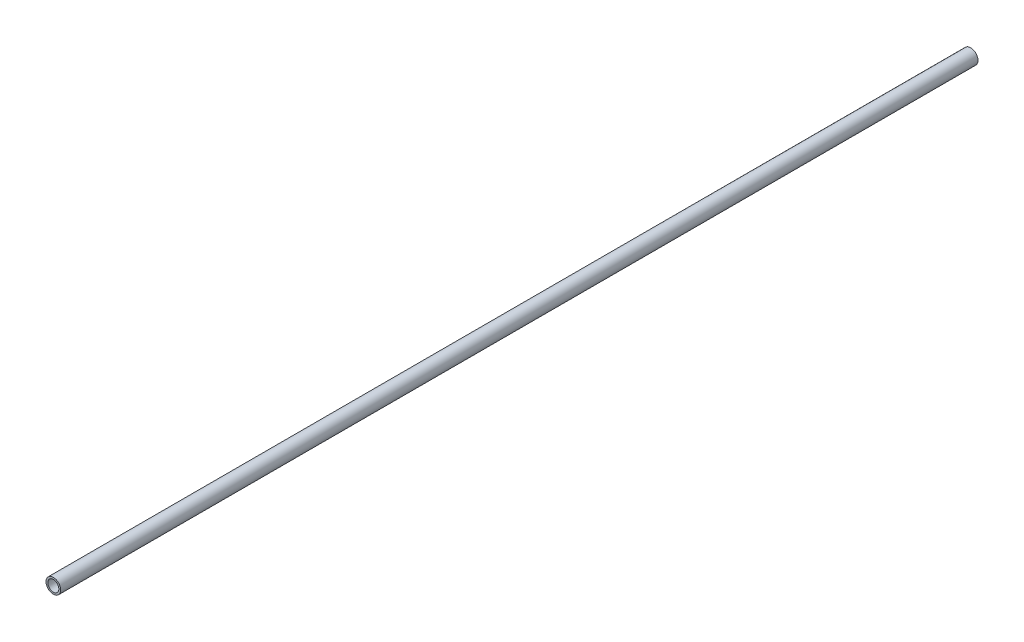
SolidWorks part; units mm, degrees
ref_plane "Płaszczyzna przednia" through (0, 0, 0) normal (0, 0, 1) x (1, 0, 0)
ref_plane "Płaszczyzna górna" through (0, 0, 0) normal (0, 1, 0) x (1, 0, 0)
ref_plane "Płaszczyzna prawa" through (0, 0, 0) normal (1, 0, 0) x (0, 0, -1)
sketch "Szkic1" plane through (0, 0, 0) normal (0, 0, 1) x (1, 0, 0)
  circle A0 centre (0, 0) radius 4
  dimension "D1" = 8
extrude "Dodanie-wyciągnięcie1" add sketch "Szkic1" along normal blind 500
sketch "Szkic2" plane through (0, 0, 500) normal (0, 0, 1) x (1, 0, 0)
  circle A0 centre (0, 0) radius 3
extrude "Wytnij-wyciągnięcie1" cut sketch "Szkic2" against normal blind 500
